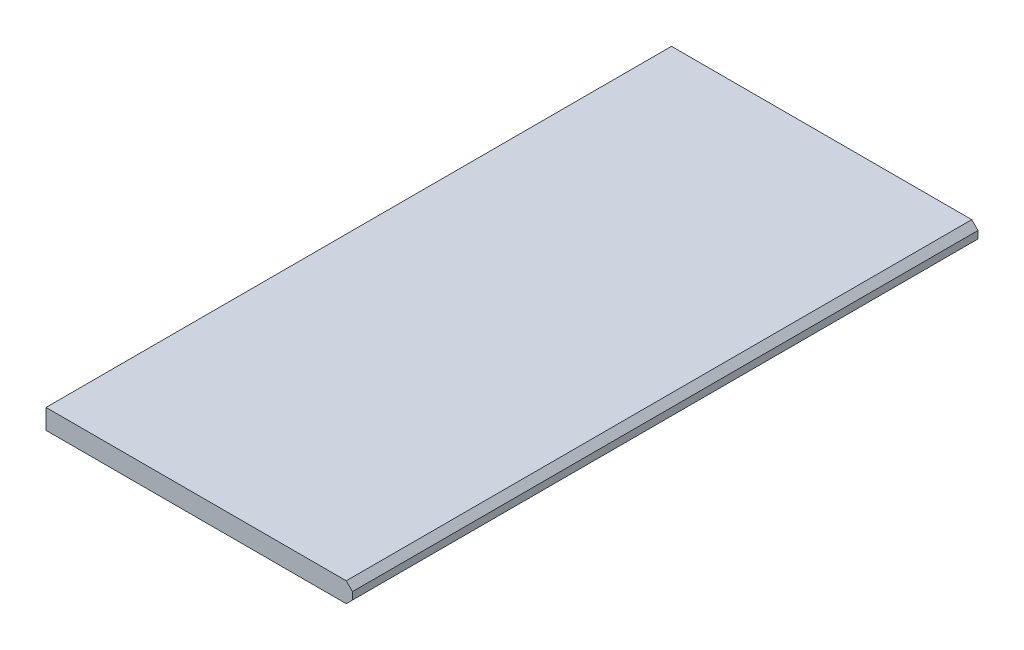
SolidWorks part; units mm, degrees
ref_plane "Front Plane" through (0, 0, 0) normal (0, 0, 1) x (1, 0, 0)
ref_plane "Top Plane" through (0, 0, 0) normal (0, 1, 0) x (1, 0, 0)
ref_plane "Right Plane" through (0, 0, 0) normal (1, 0, 0) x (0, 0, -1)
sketch "Sketch1" plane through (0, 0, 0) normal (0, 0, 1) x (1, 0, 0)
  line L1 (-12.25, 0.7937) -> (12.25, 0.7937)
  line L2 (-12.25, 0.7937) -> (-12.25, -0.7937)
  line L3 (-12.25, -0.7937) -> (12.25, -0.7937)
  line L4 (12.25, 0.7937) -> (12.25, -0.7937)
  line L5 (-12.25, 0.7937) -> (12.25, -0.7937) construction
  line L6 (-12.25, -0.7937) -> (12.25, 0.7937) construction
  point P0 (0, 0)
  dimension "D1" = 1.5875
  dimension "D2" = 24.5
extrude "Boss-Extrude1" add sketch "Sketch1" along normal blind 50
chamfer "Chamfer1" distance 0.5 angle 45 2 edges at (12.25, -0.7937, 25) (12.25, 0.7937, 25)
